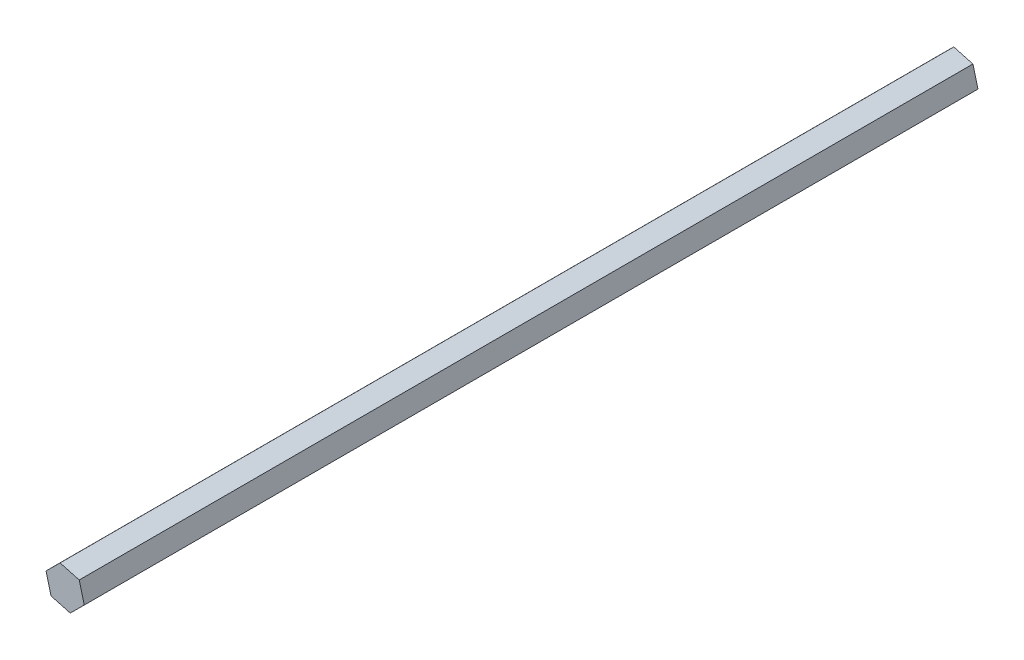
SolidWorks part; units mm, degrees
ref_plane "Front Plane" through (0, 0, 0) normal (0, 0, 1) x (1, 0, 0)
ref_plane "Top Plane" through (0, 0, 0) normal (0, 1, 0) x (1, 0, 0)
ref_plane "Right Plane" through (0, 0, 0) normal (1, 0, 0) x (0, 0, -1)
sketch "Sketch1" plane through (0, 0, 0) normal (0, 0, 1) x (1, 0, 0)
  line L1 (2.7703, -2.9333) -> (7.9724, 2.2341)
  line L2 (7.9724, 2.2341) -> (6.0984, 9.3229)
  line L3 (6.0984, 9.3229) -> (-0.9778, 11.2443)
  line L4 (-0.9778, 11.2443) -> (-6.1798, 6.0769)
  line L5 (-6.1798, 6.0769) -> (-4.3058, -1.0119)
  line L6 (-4.3058, -1.0119) -> (2.7703, -2.9333)
  circle A0 centre (0.8963, 4.1555) radius 6.35 construction
  dimension "D1" = 12.7
extrude "Boss-Extrude1" add sketch "Sketch1" along normal blind 330.2
